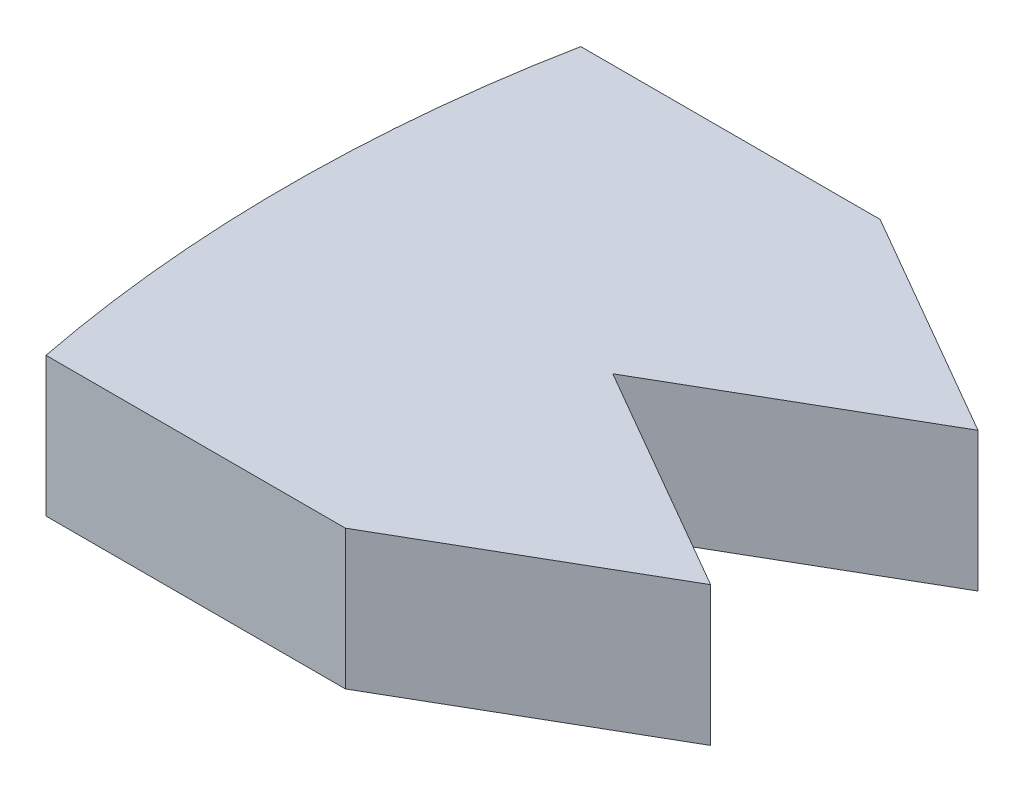
SolidWorks part; units mm, degrees
ref_plane "Front Plane" through (0, 0, 0) normal (0, 0, 1) x (1, 0, 0)
ref_plane "Top Plane" through (0, 0, 0) normal (0, 1, 0) x (1, 0, 0)
ref_plane "Right Plane" through (0, 0, 0) normal (1, 0, 0) x (0, 0, -1)
sketch "Sketch2" plane through (0, 0, 0) normal (0, 1, 0) x (1, 0, 0)
  line L0 (-50.7501, 9.4942) -> (-40.1916, 3.3982)
  line L1 (-40.1916, 3.3982) -> (-50.7501, -2.6978)
  line L2 (-50.7501, -2.6978) -> (-40.1916, -8.7938)
  line L3 (-40.1916, -8.7938) -> (-50.7501, -14.8898)
  line L4 (-50.7501, -14.8898) -> (-64.4026, -14.8898)
  line L5 (-50.7501, 9.4942) -> (-64.4026, 9.4942)
  arc A0 (-64.4026, 9.4942) -> (-64.4026, -14.8898) centre (-2.0841, -2.6978) ccw
  dimension "D1" = 12.192
  dimension "D2" = 12.192
  dimension "D3" = 13.6525
extrude "Boss-Extrude1" add sketch "Sketch2" along normal blind 6.35
